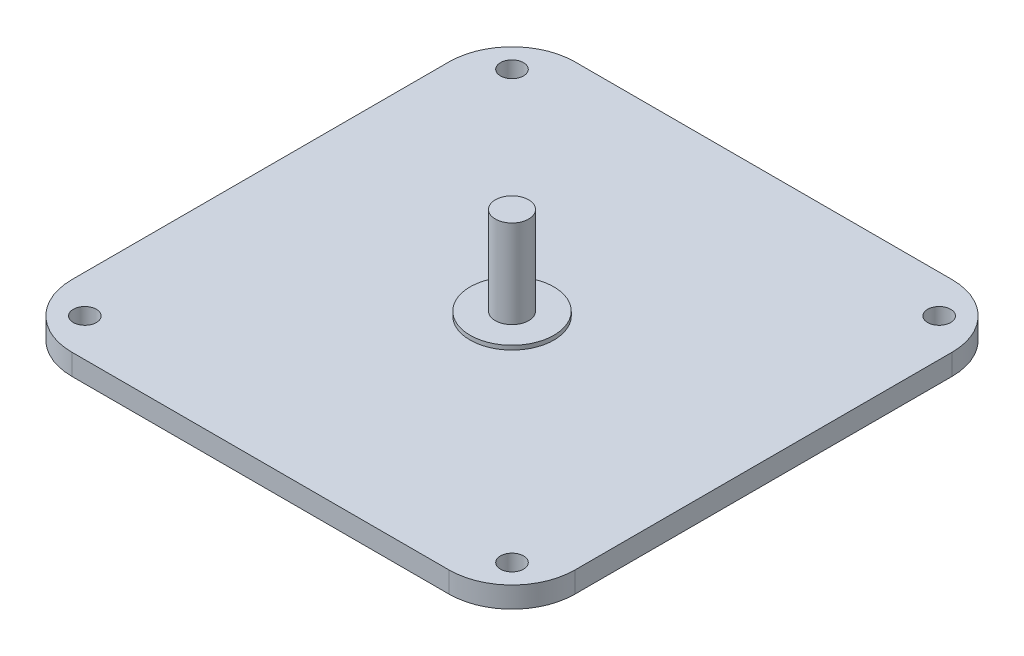
SolidWorks part; units mm, degrees
ref_plane "Plano frontal" through (0, 0, 0) normal (0, 0, 1) x (1, 0, 0)
ref_plane "Plano superior" through (0, 0, 0) normal (0, 1, 0) x (1, 0, 0)
ref_plane "Plano direito" through (0, 0, 0) normal (1, 0, 0) x (0, 0, -1)
sketch "Esboço1" plane through (0, 0, 0) normal (0, 1, 0) x (1, 0, 0)
  line L0 (60, 60) -> (-60, -60) construction
  line L1 (-60, -60) -> (60, -60)
  line L2 (-60, -60) -> (-60, 60)
  line L3 (-60, 60) -> (60, 60)
  line L4 (60, -60) -> (60, 60)
  line L5 (60, -60) -> (-60, 60) construction
  circle A9 centre (50.9554, -50.9554) radius 2.75
  circle A10 centre (50.9554, 50.9554) radius 2.75
  circle A11 centre (-50.9554, 50.9554) radius 2.75
  circle A12 centre (-50.9554, -50.9554) radius 2.75
  point P0 (0, 0)
  point P16 (0, 0)
  point P19 (0, 0)
  dimension "D3" = 5.5
  dimension "D4" = 9.0446
  dimension "D1" = 120
  dimension "D2" = 120
  dimension "D5" = 9.0446
extrude "Ressalto-extrusão1" add sketch "Esboço1" along normal mid plane 5 contours L1 L4 L3 L2 A12 A11 A10 A9
fillet "Filete1" radius 15 4 edges at (-60, 0, -60) (60, 0, -60) (60, 0, 60) (-60, 0, 60)
sketch "Esboço2" plane through (0, 2.5, 0) normal (0, 1, 0) x (1, 0, 0)
  circle A2 centre (0, 0) radius 3.975
  dimension "D1" = 7.95
extrude "Ressalto-extrusão2" add sketch "Esboço2" along normal blind 22
sketch "Esboço3" plane through (0, 2.5, 0) normal (0, 1, 0) x (1, 0, 0)
  circle A0 centre (0, 0) radius 10
  dimension "D1" = 20
extrude "Ressalto-extrusão3" add sketch "Esboço3" along normal blind 1
move or copy body "Corpo-Converter em corpo de malha1" [suppressed] bodies to move or copy 103 copy no translate (0, 0, 0) parameters "D1"=0, "D2"=0, "D3"=0
